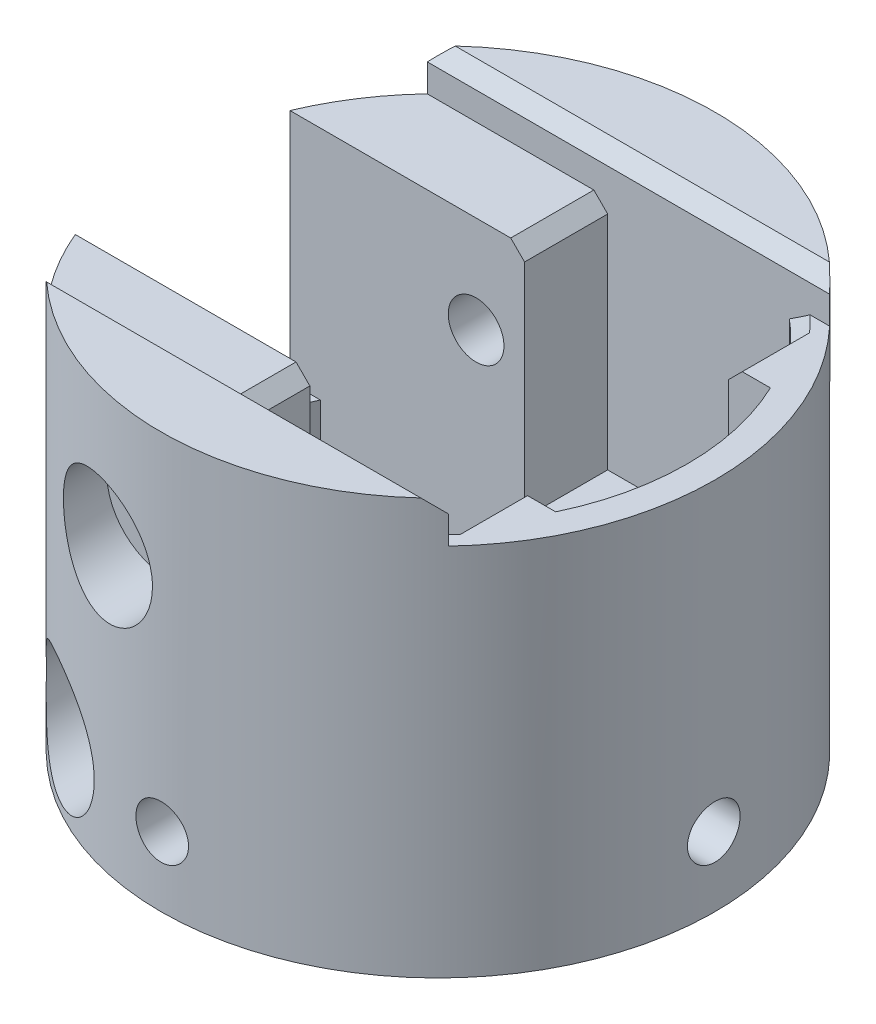
SolidWorks part; units mm, degrees
ref_plane "Front Plane" through (0, 0, 0) normal (0, 0, 1) x (1, 0, 0)
ref_plane "Top Plane" through (0, 0, 0) normal (0, 1, 0) x (1, 0, 0)
ref_plane "Right Plane" through (0, 0, 0) normal (1, 0, 0) x (0, 0, -1)
sketch "Sketch1" plane through (0, 0, 0) normal (0, 1, 0) x (1, 0, 0)
  line L1 (-14.7527, 17.4625) -> (14.7527, 17.4625) construction
  line L2 (0, 17.4625) -> (0, -17.4625) construction
  line L3 (-14.7527, -17.4625) -> (14.7527, -17.4625) construction
  line L4 (0, 0) -> (0, -25.4) construction
  line L5 (14.7527, 17.4625) -> (-1.905, 17.4625) construction
  line L6 (-1.905, 17.4625) -> (-1.905, 9.8425) construction
  line L7 (-1.905, 9.8425) -> (-20.6326, 9.8425)
  line L8 (14.7527, -17.4625) -> (-1.905, -17.4625) construction
  line L9 (-1.905, -17.4625) -> (-1.905, -9.8425) construction
  line L10 (-1.905, -9.8425) -> (-20.6326, -9.8425)
  line L11 (0, 0) -> (-11.2688, 0) construction
  line L12 (-11.2688, 9.8425) -> (-11.2688, -9.8425) construction
  line L13 (-0.635, 8.4044) -> (15.875, 8.4044) construction
  line L18 (16.7847, 15.5195) -> (16.7847, 9.8425) construction
  line L19 (16.7847, 9.8425) -> (20.6326, 9.8425) construction
  line L20 (-1.905, 9.8425) -> (16.7847, 9.8425) construction
  line L21 (16.7847, -15.5195) -> (16.7847, -9.8425) construction
  line L22 (16.7847, -9.8425) -> (-1.905, -9.8425) construction
  line L23 (16.7847, -9.8425) -> (20.6326, -9.8425) construction
  line L27 (16.7847, 9.8425) -> (16.7847, -9.8425)
  line L28 (16.7847, 9.8425) -> (-1.905, 9.8425)
  line L29 (16.7847, -9.8425) -> (-1.905, -9.8425)
  circle A0 centre (0, 0) radius 25.4
  circle A1 centre (0, 0) radius 22.86 construction
  arc A4 (-20.6326, 9.8425) -> (-20.6326, -9.8425) centre (0, 0) ccw
  arc A5 (14.7527, 17.4625) -> (16.7847, 15.5195) centre (0, 0) cw construction
  arc A7 (14.7527, -17.4625) -> (16.7847, -15.5195) centre (0, 0) ccw construction
  point P9 (0, -17.4625)
  point P10 (0, 0)
  point P22 (7.62, 8.4044)
  point P23 (-11.2688, 0)
  point P28 (-11.2688, 9.8425)
  dimension "D1" = 50.8
  dimension "D2" = 2.54
  dimension "D3" = 34.925
  dimension "D4" = 1.905
  dimension "D7" = 7.62
  dimension "D9" = 2.032
  dimension "D10" = 2.032
  dimension "D11" = 16.6577
  dimension "D5" = 19.685
  dimension "D6" = 29.5053
  dimension "D8" = 16.51
extrude "base_ring" add sketch "Sketch1" along normal blind 12.7
ref_plane "set_screw_plane" through (0, 0, 25.4) normal (0, 0, 1) x (1, 0, 0)
ref_plane "midplane" through (0, 0, 0) normal (0, 0, 1) x (1, 0, 0)
sketch "set_screw" plane through (0, 0, 25.4) normal (0, 0, 1) x (1, 0, 0)
  line L0 (0, 6.35) -> (0, 0) construction
  circle A0 centre (0, 6.35) radius 2.413
  point P7 (-12.7, 6.35)
  dimension "D1" = 4.826
  dimension "D2" = 6.35
extrude "set_screw_hole" cut sketch "set_screw" against normal blind 19.05 contours A0
pattern_circular "set_screw_pattern" count 3 every 90 about axis through (0, 12.7, 0) along (0, -1, 0) of "set_screw_hole"
sketch "Sketch4" plane through (0, 0, 25.4) normal (0, 0, 1) x (1, 0, 0)
  line L0 (22.86, 0) -> (-22.86, 0) construction
  point P0 (-12.7, 6.35)
  dimension "D1" = 6.35
  dimension "D2" = 12.7
sketch "Sketch6" plane through (0, 12.7, 0) normal (0, 1, 0) x (1, 0, 0)
  line L0 (-23.4155, 9.8425) -> (-1.905, 9.8425)
  line L1 (-23.4155, -9.8425) -> (-1.905, -9.8425)
  line L2 (-1.905, 9.8425) -> (-1.905, 17.4625)
  line L3 (-1.905, 17.4625) -> (14.7527, 17.4625)
  line L4 (-1.905, -9.8425) -> (-1.905, -17.4625)
  line L5 (-1.905, -17.4625) -> (14.7527, -17.4625)
  line L8 (16.7847, -15.5195) -> (16.7847, -9.8425)
  line L10 (16.7847, -9.8425) -> (20.6326, -9.8425)
  line L11 (16.7847, 15.5195) -> (16.7847, 9.8425)
  line L12 (16.7847, 9.8425) -> (20.6326, 9.8425)
  line L13 (-1.905, 17.4625) -> (-1.905, 9.8425) construction
  circle A0 centre (0, 0) radius 25.4 construction
  arc A1 (-23.4155, 9.8425) -> (-23.4155, -9.8425) centre (0, 0) cw
  arc A2 (14.7527, -17.4625) -> (16.7847, -15.5195) centre (0, 0) ccw
  arc A4 (14.7527, 17.4625) -> (16.7847, 15.5195) centre (0, 0) cw
  circle A5 centre (0, 0) radius 25.4 construction
  arc A6 (20.6326, 9.8425) -> (20.6326, -9.8425) centre (0, 0) cw
extrude "upper_section" add sketch "Sketch6" along normal blind 21.59
hole_wizard "lower_axle" positions "Sketch4" profile "Sketch5" counterbore size "#10" standard "ANSI Inch"
sketch "Sketch5" plane through (-12.7, 6.35, 25.4) normal (1, 0, 0) x (0, -1, 0)
  line L0 (0, 0) -> (0, 15.5575)
  line L1 (0, 15.5575) -> (2.5527, 15.5575)
  line L3 (2.5527, 15.5575) -> (2.5527, 10.7442)
  line L4 (2.5527, 10.7442) -> (5.5562, 10.7442)
  line L5 (5.5562, 10.7442) -> (5.5562, 0)
  line L7 (5.5562, 0) -> (0, 0)
  line L11 (0, -6.35) -> (0, 107.95) construction
  dimension "Thru Hole Dia." = 5.1054
  dimension "Thru Hole Depth" = 15.5575
  dimension "C'Bore Dia." = 11.1125
  dimension "C'Bore Depth" = 10.7442
sketch "Sketch7" plane through (0, 0, 25.4) normal (0, 0, 1) x (1, 0, 0)
  point P0 (-6.35, 25.4)
  dimension "D1" = 19.05
  dimension "D2" = 6.35
hole_wizard "upper_axle" positions "Sketch7" profile "Sketch8" counterbore size "#10" standard "ANSI Inch"
sketch "Sketch8" plane through (-6.35, 25.4, 25.4) normal (1, 0, 0) x (0, -1, 0)
  line L0 (0, 0) -> (0, 15.5575)
  line L1 (0, 15.5575) -> (2.5527, 15.5575)
  line L3 (2.5527, 15.5575) -> (2.5527, 6.9342)
  line L4 (2.5527, 6.9342) -> (5.5562, 6.9342)
  line L5 (5.5562, 6.9342) -> (5.5562, 0)
  line L7 (5.5562, 0) -> (0, 0)
  line L11 (0, -6.35) -> (0, 107.95) construction
  dimension "Thru Hole Dia." = 5.1054
  dimension "Thru Hole Depth" = 15.5575
  dimension "C'Bore Dia." = 11.1125
  dimension "C'Bore Depth" = 6.9342
sketch "Sketch10" plane through (0, 0, 0) normal (0, -1, 0) x (1, 0, 0)
  line L0 (8.89, 23.7934) -> (8.89, 9.8425) construction
  line L1 (-20.6326, 9.8425) -> (16.7847, 9.8425) construction
  circle A0 centre (8.89, 13.97) radius 2.413
  circle A3 centre (0, 0) radius 25.4 construction
  dimension "D1" = 4.826
  dimension "D4" = 13.97
  dimension "D3" = 8.89
extrude "servo_plate_screw" cut sketch "Sketch10" against normal up to next
sketch "Sketch11" plane through (0, 12.7, 0) normal (0, 1, 0) x (1, 0, 0)
  line L1 (14.7559, -13.97) -> (11.8229, -8.89)
  line L2 (11.8229, -8.89) -> (5.9571, -8.89)
  line L3 (5.9571, -8.89) -> (3.0241, -13.97)
  line L4 (3.0241, -13.97) -> (5.9571, -19.05)
  line L5 (5.9571, -19.05) -> (11.8229, -19.05)
  line L6 (11.8229, -19.05) -> (14.7559, -13.97)
  circle A0 centre (8.89, -13.97) radius 5.08 construction
  dimension "D1" = 10.16
extrude "nut_hole" cut sketch "Sketch11" against normal blind 2.54 and the other way blind 2.54
sketch "Sketch12" plane through (0, 0, 9.8425) normal (0, 0, -1) x (-1, 0, 0)
  line L1 (5.08, 3.4171) -> (5.08, 9.2829)
  line L2 (5.08, 9.2829) -> (0, 12.2159)
  line L3 (0, 12.2159) -> (-5.08, 9.2829)
  line L4 (-5.08, 9.2829) -> (-5.08, 3.4171)
  line L5 (-5.08, 3.4171) -> (0, 0.4841)
  line L6 (0, 0.4841) -> (5.08, 3.4171)
  circle A0 centre (0, 6.35) radius 5.08 construction
  dimension "D1" = 10.16
extrude "lower_nut_hole" cut sketch "Sketch12" against normal blind 2.54
sketch "Sketch13" plane through (16.7847, 0, 0) normal (-1, 0, 0) x (0, 0, 1)
  line L1 (0, 12.2159) -> (-5.08, 9.2829)
  line L2 (-5.08, 9.2829) -> (-5.08, 3.4171)
  line L3 (-5.08, 3.4171) -> (0, 0.4841)
  line L4 (0, 0.4841) -> (5.08, 3.4171)
  line L5 (5.08, 3.4171) -> (5.08, 9.2829)
  line L6 (5.08, 9.2829) -> (0, 12.2159)
  circle A0 centre (0, 6.35) radius 5.08 construction
  dimension "D1" = 10.16
extrude "front_nut_hole" cut sketch "Sketch13" against normal blind 2.54
mirror "screw_mirror" about plane through (0, 0, 0) normal (0, 0, 1) of "lower_nut_hole", "servo_plate_screw", "lower_axle", "upper_axle", "nut_hole"
sketch "Sketch9" plane through (0, 34.29, 0) normal (0, 1, 0) x (1, 0, 0)
  line L0 (-18.4451, 17.4625) -> (18.4451, 17.4625)
  line L1 (-18.4451, -17.4625) -> (18.4451, -17.4625)
  arc A0 (-23.4155, -9.8425) -> (-23.4155, 9.8425) centre (0, 0) ccw construction
  arc A1 (-18.4451, 17.4625) -> (18.4451, 17.4625) centre (0, 0) cw
  arc A2 (-18.4451, -17.4625) -> (18.4451, -17.4625) centre (0, 0) ccw
extrude "flush_plate" add sketch "Sketch9" along normal blind 3.81
chamfer "lead_in_chamfer" distance 1.27 angle 45 8 edges at (0, 38.1, 17.4625) (0, 38.1, -17.4625) (15.7985, 34.29, 16.5223) (16.7847, 34.29, 12.681) (16.7847, 34.29, -12.681) (15.7985, 34.29, -16.5223) (-1.905, 34.29, 13.6525) (-1.905, 34.29, -13.6525)
equation "\"tapped\"= 0.19in"
